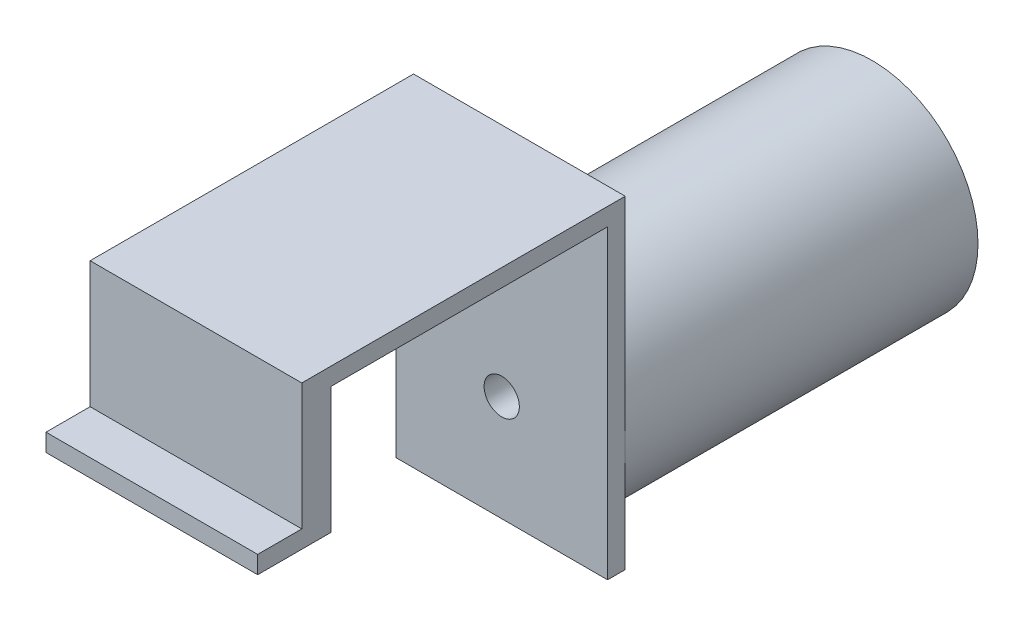
SolidWorks part; units mm, degrees
ref_plane "Front Plane" through (0, 0, 0) normal (0, 0, 1) x (1, 0, 0)
ref_plane "Top Plane" through (0, 0, 0) normal (0, 1, 0) x (1, 0, 0)
ref_plane "Right Plane" through (0, 0, 0) normal (1, 0, 0) x (0, 0, -1)
sketch "Sketch2" plane through (0, 0, 0) normal (0, 0, 1) x (1, 0, 0)
  circle A0 centre (0, 0) radius 18
extrude "Boss-Extrude1" add sketch "Sketch2" along normal blind 60
sketch "Sketch3" plane through (0, 0, 60) normal (0, 0, 1) x (1, 0, 0)
  circle A0 centre (0, 0) radius 3
  dimension "D1" = 0
sketch "Sketch4" plane through (0, 0, 60) normal (0, 0, 1) x (1, 0, 0)
  line L1 (-18, 37) -> (18, 37)
  line L2 (-18, 37) -> (-18, -18)
  line L3 (-18, -18) -> (18, -18)
  line L4 (18, 37) -> (18, -18)
  point P0 (0, 0)
  dimension "D1" = 36
  dimension "D2" = 55
  dimension "D3" = 18
extrude "Boss-Extrude2" add sketch "Sketch4" along normal blind 3
extrude "Cut-Extrude1" cut sketch "Sketch3" against normal blind 60 and the other way blind 3
sketch "Sketch6" plane through (0, 37, 0) normal (0, 1, 0) x (1, 0, 0)
  line L0 (-18, -63) -> (-18, -110)
  line L1 (-18, -110) -> (18, -110)
  line L2 (18, -110) -> (18, -63)
  line L3 (18, -63) -> (-18, -63)
  dimension "D1" = 47
extrude "Boss-Extrude3" add sketch "Sketch6" against normal blind 3
sketch "Sketch7" plane through (0, 0, 110) normal (0, 0, 1) x (1, 0, 0)
  line L1 (18, 34) -> (18, 12.5)
  line L2 (18, -18) -> (18, 34) construction
  line L3 (18, 12.5) -> (-18, 12.5)
  line L4 (-18, 34) -> (-18, -18) construction
  line L5 (-18, 12.5) -> (-18, 34)
  line L6 (-18, 37) -> (18, 37)
  line L7 (18, 37) -> (18, 34)
  line L8 (-18, 34) -> (-18, 37)
  dimension "D1" = 21.5
extrude "Boss-Extrude4" add sketch "Sketch7" along normal blind 5
sketch "Sketch8" plane through (0, 0, 115) normal (0, 0, 1) x (1, 0, 0)
  line L0 (-18, 12.5) -> (-18, 15.5)
  line L1 (-18, 37) -> (-18, 12.5) construction
  line L2 (-18, 15.5) -> (18, 15.5)
  line L3 (18, 12.5) -> (18, 37) construction
  line L4 (18, 15.5) -> (18, 12.5)
  line L5 (18, 12.5) -> (-18, 12.5)
  dimension "D1" = 3
extrude "Boss-Extrude5" add sketch "Sketch8" along normal blind 7.5
equation "\"7.5.00mm\"=20"
